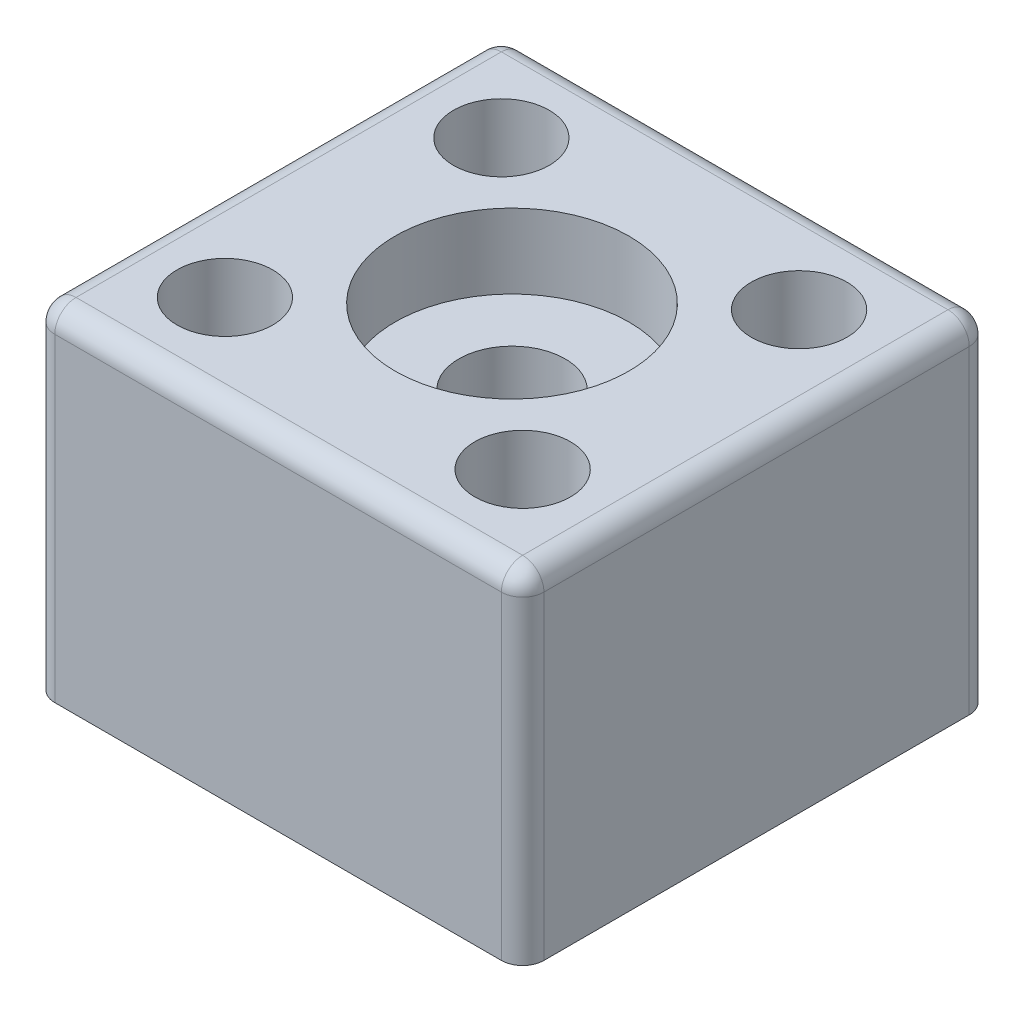
SolidWorks part; units mm, degrees
ref_plane "Front Plane" through (0, 0, 0) normal (0, 0, 1) x (1, 0, 0)
ref_plane "Top Plane" through (0, 0, 0) normal (0, 1, 0) x (1, 0, 0)
ref_plane "Right Plane" through (0, 0, 0) normal (1, 0, 0) x (0, 0, -1)
sketch "Sketch1" plane through (0, 0, 0) normal (0, 1, 0) x (1, 0, 0)
  line L1 (-23, 22) -> (23, 22)
  line L2 (-23, 22) -> (-23, -22)
  line L3 (-23, -22) -> (23, -22)
  line L4 (23, 22) -> (23, -22)
  line L5 (-23, 22) -> (23, -22) construction
  line L6 (-23, -22) -> (23, 22) construction
  point P0 (0, 0)
  dimension "D1" = 46
  dimension "D2" = 44
extrude "Boss-Extrude1" add sketch "Sketch1" along normal blind 32
sketch "Sketch2" plane through (0, 0, 0) normal (0, -1, 0) x (1, 0, 0)
  line L0 (23, -22) -> (-23, -22) construction
  line L1 (-23, -22) -> (-23, 22) construction
  circle A0 centre (-14, -13) radius 2.65
  dimension "D3" = 5.3
  dimension "D1" = 9
  dimension "D2" = 9
extrude "Cut-Extrude1" cut sketch "Sketch2" against normal through all
pattern_linear "LPattern1" count 2 spacing 26 along (0, 0, 1) count 2 spacing 28 along (1, 0, 0) of "Cut-Extrude1"
sketch "Sketch3" plane through (0, 32, 0) normal (0, 1, 0) x (1, 0, 0)
  circle A0 centre (0, 0) radius 11
  dimension "D1" = 22
extrude "Cut-Extrude2" cut sketch "Sketch3" against normal blind 7 contours A0
fillet "Fillet1" radius 2 8 edges at (0, 32, -22) (23, 32, 0) (23, 16, -22) (-23, 16, -22) (-23, 32, 0) (-23, 16, 22) (0, 32, 22) (23, 16, 22)
sketch "Sketch4" plane through (0, 32, 0) normal (0, 1, 0) x (1, 0, 0)
  circle A3 centre (14, -13) radius 4.5
  dimension "D2" = 9
extrude "Cut-Extrude3" cut sketch "Sketch4" against normal blind 22 contours A3
pattern_linear "LPattern2" count 2 spacing 28 along (-1, 0, 0) count 2 spacing 26 along (0, 0, -1) of "Cut-Extrude3"
sketch "Sketch5" plane through (0, 32, 0) normal (0, 1, 0) x (1, 0, 0)
  circle A0 centre (0, 0) radius 5
  dimension "D1" = 10
extrude "Cut-Extrude4" cut sketch "Sketch5" against normal through all contours A0
